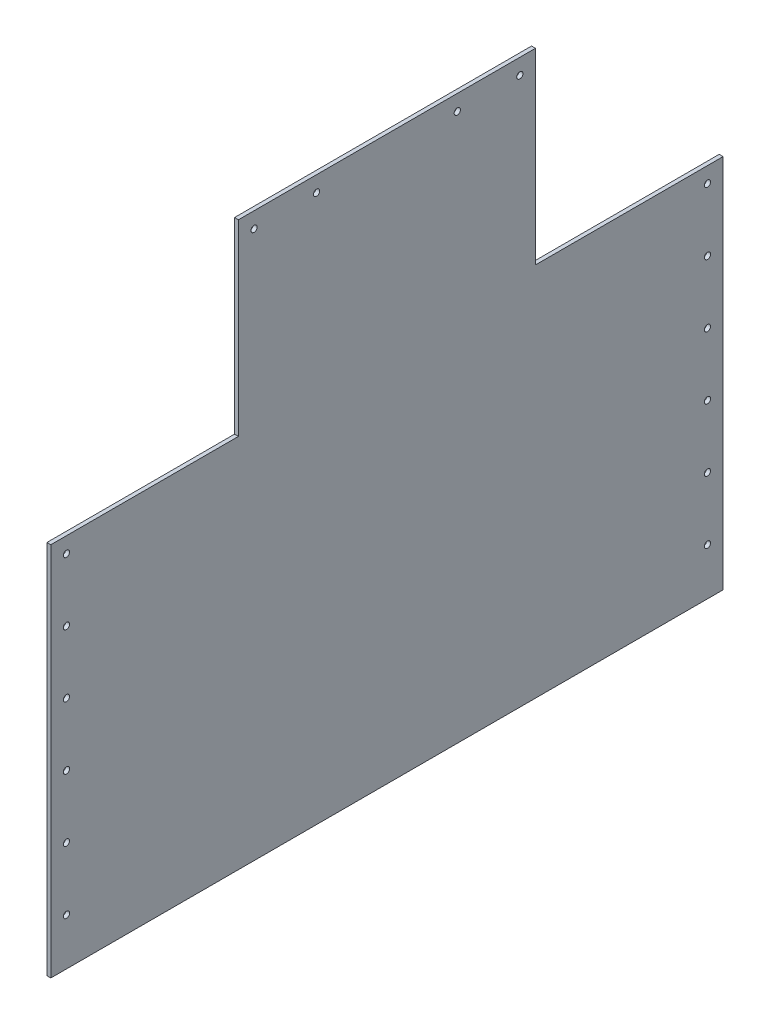
SolidWorks part; units mm, degrees
ref_plane "Front Plane" through (0, 0, 0) normal (0, 0, 1) x (1, 0, 0)
ref_plane "Top Plane" through (0, 0, 0) normal (0, 1, 0) x (1, 0, 0)
ref_plane "Right Plane" through (0, 0, 0) normal (1, 0, 0) x (0, 0, -1)
sketch "Sketch1" plane through (0, 0, 0) normal (1, 0, 0) x (0, 0, -1)
  line L0 (0, 0) -> (0, 457.2)
  line L1 (0, 457.2) -> (546.1, 457.2)
  line L3 (546.1, 457.2) -> (546.1, 0)
  line L4 (546.1, 0) -> (0, 0)
  dimension "D1" = 546.1
  dimension "D4" = 457.2
extrude "Boss-Extrude1" add sketch "Sketch1" along normal blind 3.175
sketch "Sketch2" plane through (3.175, 0, 0) normal (1, 0, 0) x (0, 0, -1)
  line L2 (0, 0) -> (546.1, 0) construction
  line L3 (273.05, 457.2) -> (273.05, 0) construction
  line L4 (546.1, 457.2) -> (0, 457.2) construction
  line L5 (0, 457.2) -> (0, 0) construction
  circle A96 centre (12.7, 444.5) radius 2.54
  circle A97 centre (63.5, 444.5) radius 2.54
  circle A98 centre (114.3, 444.5) radius 2.54
  circle A99 centre (165.1, 444.5) radius 2.54
  circle A100 centre (215.9, 444.5) radius 2.54
  circle A101 centre (12.7, 393.7) radius 2.54
  circle A102 centre (12.7, 342.9) radius 2.54
  circle A103 centre (12.7, 292.1) radius 2.54
  circle A104 centre (12.7, 241.3) radius 2.54
  circle A105 centre (12.7, 190.5) radius 2.54
  circle A106 centre (12.7, 139.7) radius 2.54
  circle A107 centre (12.7, 88.9) radius 2.54
  circle A108 centre (12.7, 38.1) radius 2.54
  circle A109 centre (533.4, 38.1) radius 2.54
  circle A110 centre (533.4, 88.9) radius 2.54
  circle A111 centre (533.4, 139.7) radius 2.54
  circle A112 centre (533.4, 190.5) radius 2.54
  circle A113 centre (533.4, 241.3) radius 2.54
  circle A114 centre (533.4, 292.1) radius 2.54
  circle A115 centre (533.4, 342.9) radius 2.54
  circle A116 centre (533.4, 393.7) radius 2.54
  circle A117 centre (330.2, 444.5) radius 2.54
  circle A118 centre (381, 444.5) radius 2.54
  circle A119 centre (431.8, 444.5) radius 2.54
  circle A120 centre (482.6, 444.5) radius 2.54
  circle A121 centre (533.4, 444.5) radius 2.54
  dimension "D1" = 5.08
  dimension "D2" = 12.7
  dimension "D3" = 12.7
extrude "Cut-Extrude1" cut sketch "Sketch2" against normal through all
sketch "Sketch4" plane through (3.175, 0, 0) normal (1, 0, 0) x (0, 0, -1)
  line L0 (273.05, 457.2) -> (273.05, 0) construction
  line L1 (0, 457.2) -> (152.4, 457.2)
  line L2 (0, 457.2) -> (0, 304.8)
  line L3 (0, 304.8) -> (152.4, 304.8)
  line L4 (152.4, 457.2) -> (152.4, 304.8)
  line L5 (546.1, 457.2) -> (0, 457.2) construction
  line L6 (0, 0) -> (546.1, 0) construction
  line L7 (393.7, 457.2) -> (393.7, 304.8)
  line L8 (546.1, 304.8) -> (393.7, 304.8)
  line L9 (546.1, 457.2) -> (546.1, 304.8)
  line L10 (546.1, 457.2) -> (393.7, 457.2)
  dimension "D1" = 152.4
extrude "Cut-Extrude2" cut sketch "Sketch4" against normal through all
